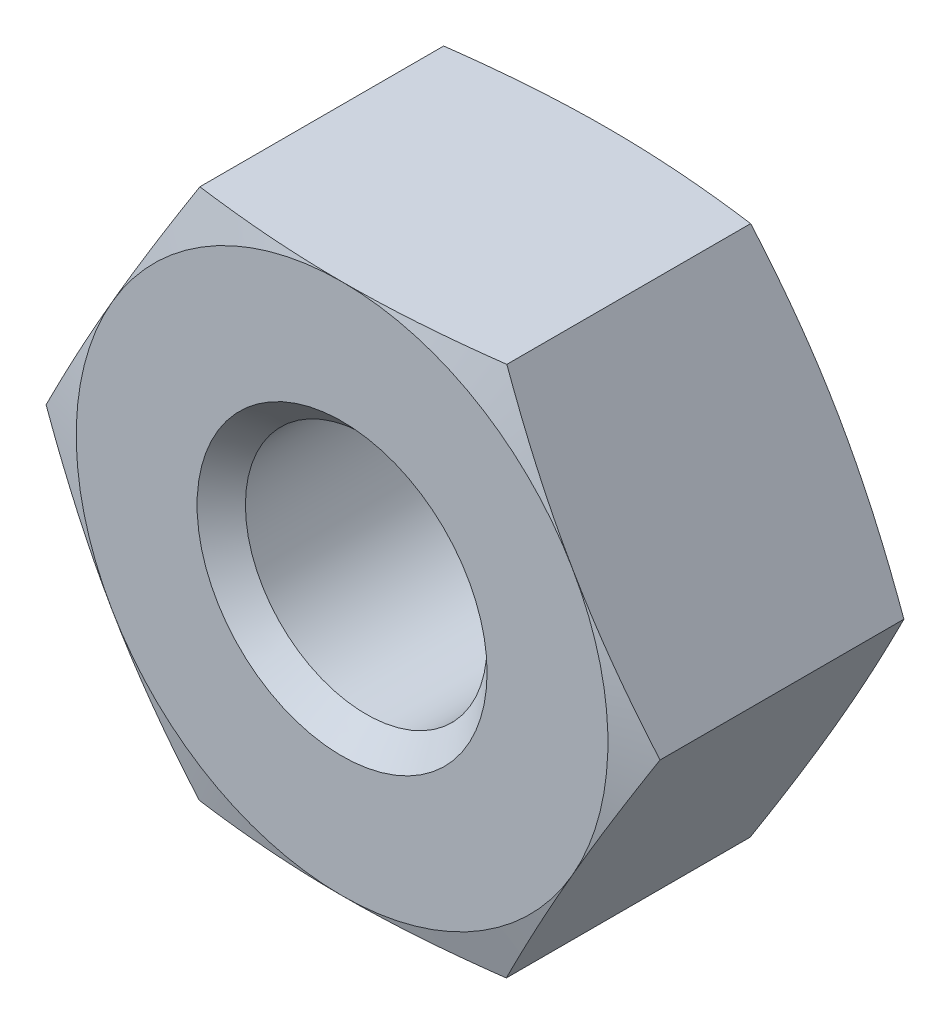
SolidWorks part; units mm, degrees
ref_plane "Plano frontal" through (0, 0, 0) normal (0, 0, 1) x (1, 0, 0)
ref_plane "Plano superior" through (0, 0, 0) normal (0, 1, 0) x (1, 0, 0)
ref_plane "Plano direito" through (0, 0, 0) normal (1, 0, 0) x (0, 0, -1)
sketch "Esboço2" plane through (0, 0, 0) normal (0, 0, 1) x (1, 0, 0)
  line L1 (3.1809, 5.4968) -> (-3.1699, 5.5032)
  line L2 (-3.1699, 5.5032) -> (-6.3508, 0.0064)
  line L3 (-6.3508, 0.0064) -> (-3.1809, -5.4968)
  line L4 (-3.1809, -5.4968) -> (3.1699, -5.5032)
  line L5 (3.1699, -5.5032) -> (6.3508, -0.0064)
  line L6 (6.3508, -0.0064) -> (3.1809, 5.4968)
  circle A0 centre (0, 0) radius 5.5 construction
  dimension "D1" = 11
extrude "Ressalto-extrusão2" add sketch "Esboço2" along normal blind 5.5
sketch "Esboço3" plane through (0, 0, 5.5) normal (0, 0, 1) x (1, 0, 0)
  circle A0 centre (0, 0) radius 5.5
extrude "Corte-extrusão1" cut sketch "Esboço3" against normal blind 13 draft 75 flip side to cut
sketch "Esboço4" plane through (0, 0, 0) normal (0, 0, -1) x (-1, 0, 0)
  circle A0 centre (0, 0) radius 5.5
extrude "Corte-extrusão2" cut sketch "Esboço4" against normal blind 13 draft 75 flip side to cut
hole_wizard "Furo roscado de M61" positions "Esboço5" profile "Esboço6" tap size "M6" standard "DIN" end condition through all
sketch "Esboço5" plane through (0, 0, 0) normal (0, 0, -1) x (-1, 0, 0)
  point P0 (0, 0)
sketch "Esboço6" plane through (0, 0, 0) normal (1, 0, 0) x (0, 1, 0)
  line L0 (0, 0) -> (0, 5.5)
  line L1 (0, 5.5) -> (2.5, 5.5)
  line L2 (2.5, 5.5) -> (2.5, 0.525)
  line L3 (2.5, 0.525) -> (3.025, 0)
  line L5 (3.025, 0) -> (0, 0)
  line L6 (-2.5, 0.525) -> (-3.025, 0) construction
  line L11 (0, -6.35) -> (0, 107.95) construction
  dimension "Thru Tap Drill Dia." = 5
  dimension "Thru Tap Drill Depth" = 5.5
  dimension "Near C'Sink Dia." = 6.05
  dimension "Near C'Sink Angle" = 90
cosmetic thread "Rosca de furo1" parameters "D2"=6
chamfer "Chanfro1" distance 0.5 angle 45 1 edges at (-2.5, 0, 5.5)
